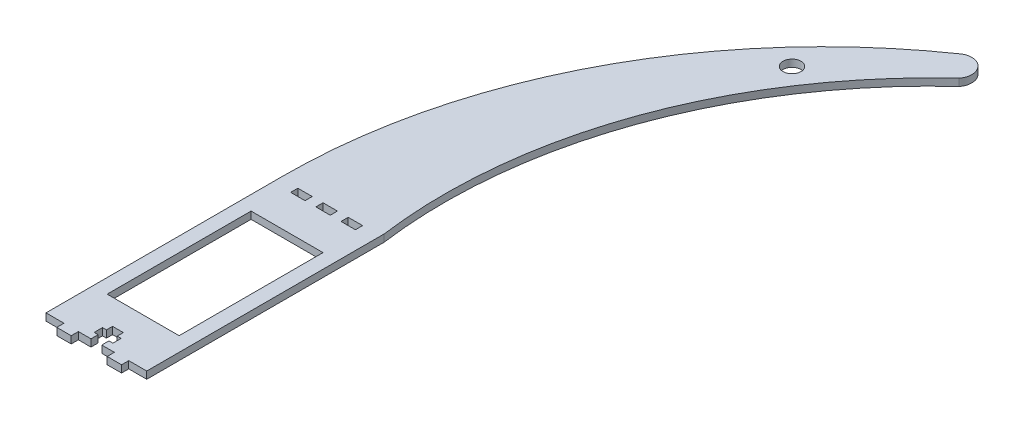
SolidWorks part; units mm, degrees
ref_plane "Front Plane" through (0, 0, 0) normal (0, 0, 1) x (1, 0, 0)
ref_plane "Top Plane" through (0, 0, 0) normal (0, 1, 0) x (1, 0, 0)
ref_plane "Right Plane" through (0, 0, 0) normal (1, 0, 0) x (0, 0, -1)
sketch "Sketch1" plane through (0, 0, 0) normal (0, 1, 0) x (1, 0, 0)
  line L0 (0, 33) -> (28, 33) construction
  line L1 (0, 0) -> (5, 0)
  line L2 (0, 0) -> (0, 66)
  line L3 (0, 66) -> (28, 66)
  line L4 (28, 0) -> (28, 66)
  line L5 (14, 66) -> (14, 0) construction
  line L6 (14, 57.25) -> (18.75, 57.25) construction
  line L7 (4, 13) -> (24, 13)
  line L8 (4, 13) -> (4, 53)
  line L9 (4, 53) -> (24, 53)
  line L10 (24, 13) -> (24, 53)
  line L11 (4, 13) -> (24, 53) construction
  line L12 (4, 53) -> (24, 13) construction
  line L13 (5, 0) -> (5, -2)
  line L19 (12.5, 6) -> (15.5, 6)
  line L20 (12.5, 6) -> (12.5, 4.3)
  line L33 (15.5, 6) -> (15.5, 4.3)
  line L34 (12.5, 6) -> (15.5, 0) construction
  line L35 (12.5, 0) -> (15.5, 6) construction
  line L36 (15.5, 2) -> (16.6, 2)
  line L38 (15.5, 4.3) -> (16.6, 4.3)
  line L39 (16.6, 2) -> (16.6, 4.3)
  line L41 (19, 0) -> (19, -2)
  line L42 (19, -2) -> (23, -2)
  line L43 (23, 0) -> (23, -2)
  line L44 (9, -2) -> (5, -2)
  line L45 (9, 0) -> (9, -2)
  line L46 (12.5, 2) -> (11.4, 2)
  line L47 (11.4, 2) -> (11.4, 4.3)
  line L48 (12.5, 4.3) -> (11.4, 4.3)
  line L49 (9, 0) -> (12.5, 0)
  line L50 (23, 0) -> (28, 0)
  line L51 (12.5, 2) -> (12.5, 0)
  line L52 (15.5, 2) -> (15.5, 0)
  line L53 (15.5, 0) -> (19, 0)
  line L54 (14, 64) -> (21, 64) construction
  line L55 (5, 65) -> (9, 65)
  line L56 (23, 63) -> (19, 63)
  line L57 (23, 63) -> (23, 65)
  line L58 (23, 65) -> (19, 65)
  line L59 (19, 63) -> (19, 65)
  line L60 (23, 63) -> (19, 65) construction
  line L61 (23, 65) -> (19, 63) construction
  line L62 (9, 63) -> (9, 65)
  line L63 (5, 63) -> (9, 63)
  line L64 (5, 63) -> (5, 65)
  line L66 (12, 63) -> (16, 63)
  line L67 (12, 63) -> (12, 65)
  line L68 (12, 65) -> (16, 65)
  line L69 (16, 63) -> (16, 65)
  line L70 (12, 63) -> (16, 65) construction
  line L71 (12, 65) -> (16, 63) construction
  point P9 (14, 33)
  point P23 (14, 3)
  point P36 (19, -1)
  dimension "D8" = 5
  dimension "D1" = 28
  dimension "D2" = 66
  dimension "D3" = 20
  dimension "D4" = 40
  dimension "D6" = 4.75
  dimension "D7" = 4.25
  dimension "D9" = 4
  dimension "D10" = 2
  dimension "D11" = 3
  dimension "D12" = 6
  dimension "D13" = 1.1
  dimension "D14" = 2.3
  dimension "D15" = 2
  dimension "D16" = 4
  dimension "D17" = 2
  dimension "D19" = 5
  dimension "D20" = 1
extrude "Boss-Extrude1" add sketch "Sketch1" along normal blind 2
sketch "Sketch2" plane through (0, 2, 0) normal (0, 1, 0) x (1, 0, 0)
  line L0 (0, 66) -> (150, 66) construction
  line L1 (150, 66) -> (28, 66) construction
  line L2 (0, 66) -> (161.7933, 84.01) construction
  line L3 (161.7933, 84.01) -> (28, 66) construction
  line L4 (64.776, 189.4377) -> (70.3785, 183.3496) construction
  line L5 (0, 66) -> (28, 66)
  arc A0 (64.776, 189.4377) -> (0, 66) centre (150, 66) ccw
  arc A1 (70.3785, 183.3496) -> (28, 66) centre (161.7933, 84.01) ccw
  arc A2 (64.776, 189.4377) -> (70.3785, 183.3496) centre (67.1495, 186) cw
  point P6 (64.776, 189.4377)
  point P8 (125.0223, 213.9058)
  dimension "D1" = 300
  dimension "D2" = 270
  dimension "D3" = 120
extrude "Boss-Extrude2" add sketch "Sketch2" against normal blind 2
sketch "Sketch3" plane through (0, 2, 0) normal (0, 1, 0) x (1, 0, 0)
  line L0 (39.4051, 167.335) -> (49.3138, 158.665) construction
  line L1 (24, 53) -> (4, 53) construction
  arc A0 (64.776, 189.4377) -> (0, 66) centre (150, 66) ccw construction
  arc A1 (70.3785, 183.3496) -> (28, 66) centre (161.7933, 84.01) ccw construction
  circle A2 centre (44.3595, 163) radius 2.5
  dimension "D1" = 5
  dimension "D2" = 110
extrude "Cut-Extrude1" cut sketch "Sketch3" against normal blind 2
